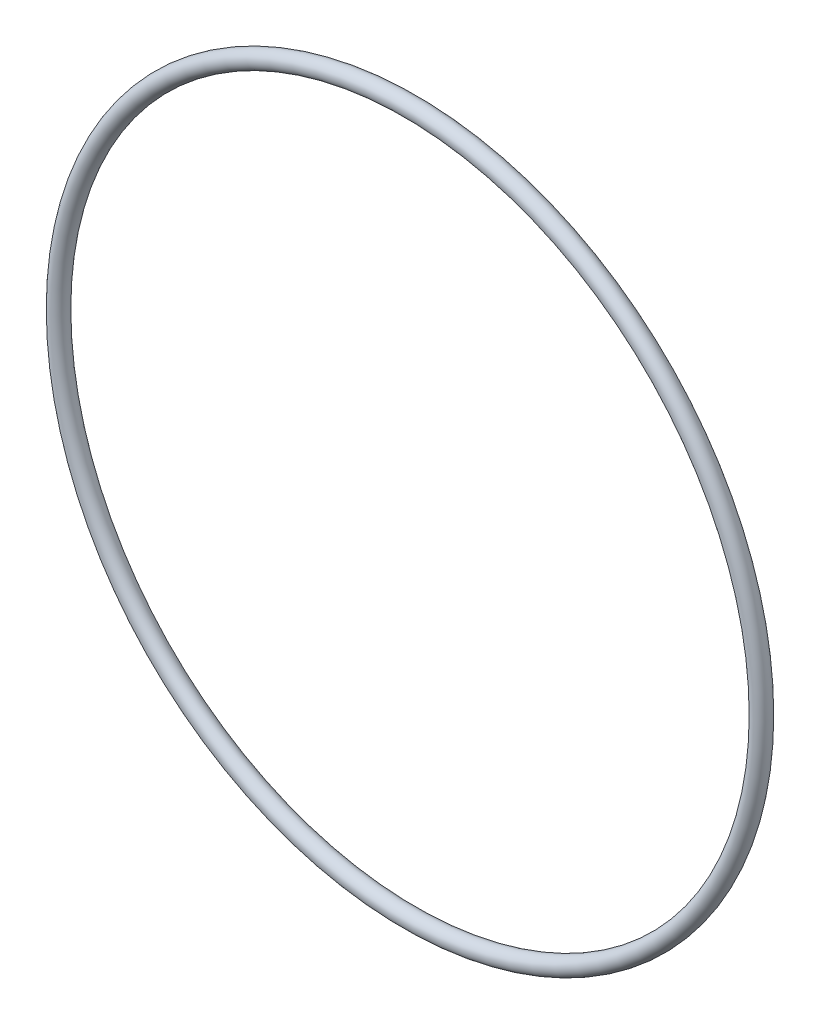
SolidWorks part; units mm, degrees
ref_plane "Front" through (0, 0, 0) normal (0, 0, 1) x (1, 0, 0)
ref_plane "Top" through (0, 0, 0) normal (0, 1, 0) x (1, 0, 0)
ref_plane "Right" through (0, 0, 0) normal (1, 0, 0) x (0, 0, -1)
sketch "Sketch1" plane through (0, 0, 0) normal (1, 0, 0) x (0, -1, 0)
  line L0 (0, -1.7653) -> (0, 1.7653) construction
  line L2 (-80.4951, 0) -> (80.4951, 0) construction
  line L3 (-69.6468, 0) -> (69.6468, 0) construction
  circle A0 centre (71.4121, 0) radius 1.7653
  point P9 (69.6468, 0)
  point P10 (73.1774, 0)
  point P13 (71.4121, 1.7653)
  point P14 (71.4121, -1.7653)
  dimension "Width" = 3.5306
  dimension "ID" = 139.2936
revolve "Revolve1" add sketch "Sketch1" angle 360 about L0
